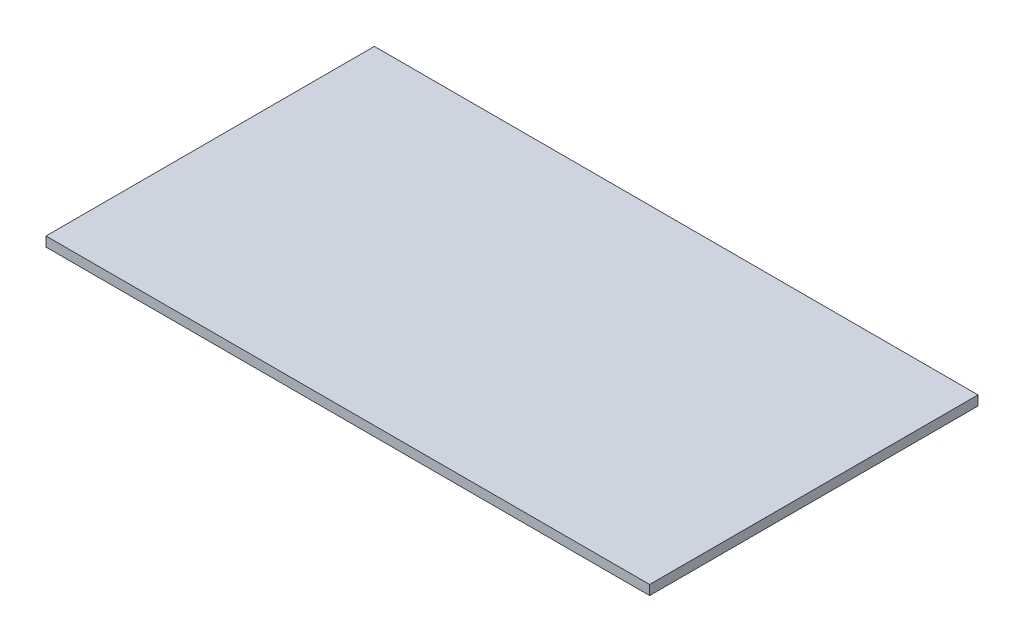
SolidWorks part; units mm, degrees
ref_plane "Front Plane" through (0, 0, 0) normal (0, 0, 1) x (1, 0, 0)
ref_plane "Top Plane" through (0, 0, 0) normal (0, 1, 0) x (1, 0, 0)
ref_plane "Right Plane" through (0, 0, 0) normal (1, 0, 0) x (0, 0, -1)
sketch "Sketch1" plane through (0, 0, 0) normal (0, 1, 0) x (1, 0, 0)
  line L1 (-132.0358, 136) -> (117.9642, 136)
  line L2 (-132.0358, 136) -> (-132.0358, 0)
  line L3 (-132.0358, 0) -> (117.9642, 0)
  line L4 (117.9642, 136) -> (117.9642, 0)
  line L5 (-132.0358, 136) -> (117.9642, 0) construction
  line L6 (-132.0358, 0) -> (117.9642, 136) construction
  point P4 (-7.0358, 68)
  dimension "D1" = 136
  dimension "D2" = 250
extrude "Boss-Extrude1" add sketch "Sketch1" along normal blind 4
